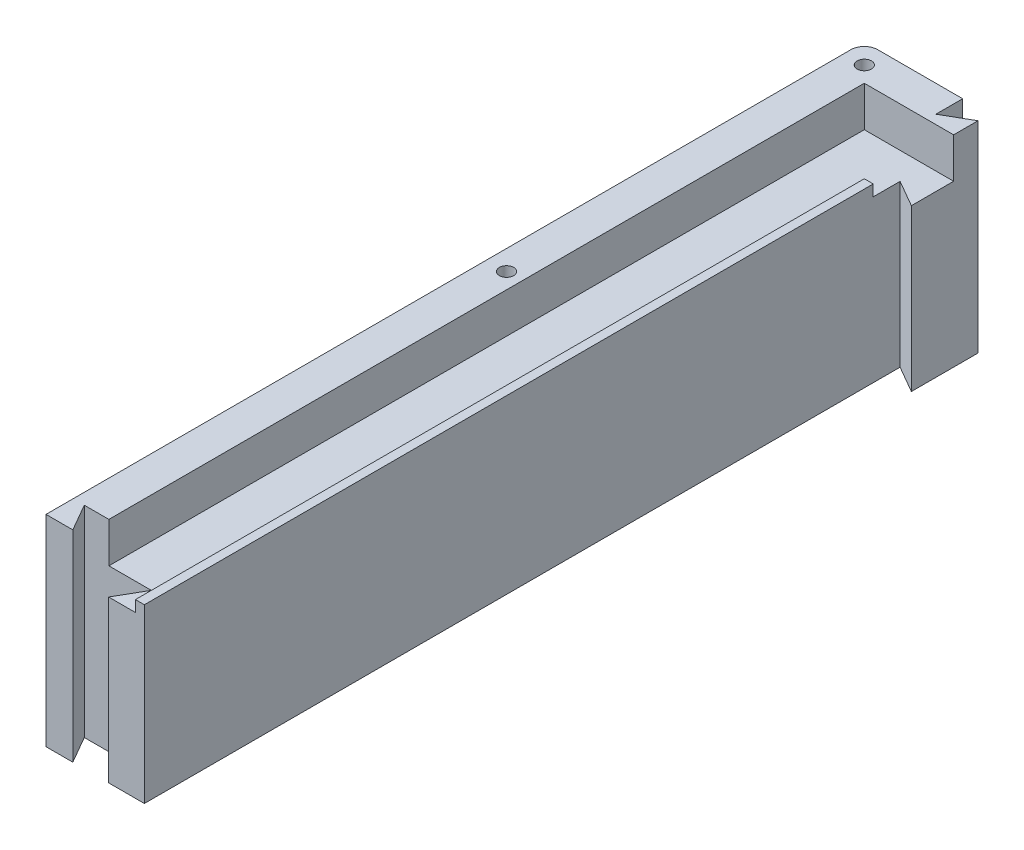
SolidWorks part; units mm, degrees
ref_plane "前视基准面" through (0, 0, 0) normal (0, 0, 1) x (1, 0, 0)
ref_plane "上视基准面" through (0, 0, 0) normal (0, 1, 0) x (1, 0, 0)
ref_plane "右视基准面" through (0, 0, 0) normal (1, 0, 0) x (0, 0, -1)
sketch "草图1" plane through (0, 0, 0) normal (0, 1, 0) x (1, 0, 0)
  line L1 (0, 0) -> (250, 0)
  line L2 (0, 0) -> (0, 350)
  line L3 (0, 350) -> (250, 350)
  line L4 (250, 0) -> (250, 350)
  line L12 (0, 350) -> (-1.1314, 351.1314)
  line L13 (-10, -10) -> (260, -10)
  line L14 (-10, -10) -> (-10, 360)
  line L15 (-10, 360) -> (260, 360)
  line L16 (260, -10) -> (260, 360)
  line L18 (14, 14) -> (236, 14)
  line L19 (14, 14) -> (14, 336)
  line L20 (14, 336) -> (236, 336)
  line L21 (236, 14) -> (236, 336)
  dimension "D7" = 135
  dimension "D1" = 350
  dimension "D2" = 250
  dimension "D3" = 10
  dimension "D4" = 10
  dimension "D5" = 10
  dimension "D6" = 10
  dimension "D8" = 14
  dimension "D9" = 14
  dimension "D10" = 14
  dimension "D11" = 14
extrude "凸台-拉伸2" add sketch "草图1" along normal blind 45
ref_plane "基准面1" through (0, 38.5, 0) normal (0, 1, 0) x (1, 0, 0)
sketch "草图4" plane through (0, 38.5, 0) normal (0, 1, 0) x (1, 0, 0)
  line L0 (0, 0) -> (250, 0) construction
  line L1 (0, 350) -> (250, 350) construction
  line L2 (250, 0) -> (250, 350) construction
  line L3 (0, 0) -> (0, 350) construction
  line L4 (0, 0) -> (250, 0)
  line L5 (0, 350) -> (250, 350)
  line L6 (250, 0) -> (250, 350)
  line L7 (0, 0) -> (0, 350)
  line L9 (14, 14) -> (236, 14)
  line L10 (14, 14) -> (14, 336)
  line L11 (14, 336) -> (236, 336)
  line L12 (236, 14) -> (236, 336)
  dimension "D1" = 14
  dimension "D2" = 14
  dimension "D3" = 14
  dimension "D4" = 14
extrude "凸台-拉伸3" add sketch "草图4" against normal blind 5
sketch "草图9" plane through (0, 38.5, 0) normal (0, 1, 0) x (1, 0, 0)
  line L0 (236, 336) -> (14, 336) construction
  line L1 (236, 14) -> (236, 336) construction
  line L2 (14, 14) -> (236, 14) construction
  line L3 (14, 336) -> (14, 14) construction
  line L4 (0, 350) -> (0, 0)
  line L5 (0, 0) -> (250, 0)
  line L6 (250, 0) -> (250, 350)
  line L7 (250, 350) -> (0, 350)
  line L8 (0, 350) -> (0, 0)
  line L9 (0, 0) -> (250, 0)
  line L10 (250, 0) -> (250, 350)
  line L11 (250, 350) -> (0, 350)
  line L12 (236, 336) -> (14, 336)
  line L13 (236, 14) -> (236, 336)
  line L14 (14, 14) -> (236, 14)
  line L15 (14, 336) -> (14, 14)
  line L16 (238, 12) -> (238, 338)
  line L17 (238, 338) -> (12, 338)
  line L18 (12, 338) -> (12, 12)
  line L19 (12, 12) -> (238, 12)
  line L20 (2, 348) -> (2, 2)
  line L21 (2, 2) -> (248, 2)
  line L22 (248, 2) -> (248, 348)
  line L23 (248, 348) -> (2, 348)
  dimension "D1" = 0
  dimension "D2" = 2
  dimension "D3" = 2
extrude "切除-拉伸3" cut sketch "草图9" against normal blind 2.5 contours L22 L23 L20 L21 L19 L18 L17 L16
sketch "草图12" plane through (0, 45, 0) normal (0, 1, 0) x (1, 0, 0)
  line L0 (0, 350) -> (-10, 360)
  line L1 (-10, 175) -> (260, 175)
  line L2 (-10, -10) -> (-10, 360) construction
  line L3 (260, -10) -> (260, 360) construction
  line L4 (125, -10) -> (125, 360)
  line L5 (-10, -10) -> (260, -10) construction
  line L6 (-10, 360) -> (260, 360) construction
  circle A0 centre (-3.5355, 353.5355) radius 1.6
  circle A1 centre (-3.5355, -3.5355) radius 1.6
  circle A2 centre (253.5355, -3.5355) radius 1.6
  circle A3 centre (253.5355, 353.5355) radius 1.6
  dimension "D1" = 3.2
  dimension "D3" = 5
extrude "切除-拉伸5" cut sketch "草图12" against normal blind 109.5 contours A1 | L0 A0 | L0 A0 | A3 | A2
fillet "圆角1" radius 5 4 edges at (260, 22.5, -360) (260, 22.5, 10) (-10, 22.5, 10) (-10, 22.5, -360)
sketch "草图13" plane through (0, 33.5, 0) normal (0, -1, 0) x (1, 0, 0)
  line L0 (14, -336) -> (14, -14) construction
  line L1 (236, -336) -> (14, -336) construction
  line L2 (14, -14) -> (236, -14) construction
  line L3 (236, -14) -> (236, -336) construction
  line L4 (0, 0) -> (0, -350)
  line L5 (0, -350) -> (250, -350)
  line L6 (250, -350) -> (250, 0)
  line L7 (250, 0) -> (0, 0)
  line L8 (0, 0) -> (0, -350)
  line L9 (0, -350) -> (250, -350)
  line L10 (250, -350) -> (250, 0)
  line L11 (250, 0) -> (0, 0)
  line L12 (14, -336) -> (14, -14)
  line L13 (236, -336) -> (14, -336)
  line L14 (14, -14) -> (236, -14)
  line L15 (236, -14) -> (236, -336)
  dimension "D1" = 0
extrude "凸台-拉伸4" add sketch "草图13" along normal blind 33.5
sketch "草图14" plane through (0, 0, 0) normal (0, -1, 0) x (1, 0, 0)
  line L0 (14, -14) -> (14, 10)
  line L1 (-5, 10) -> (255, 10) construction
  line L2 (236, -14) -> (236, 10)
  line L3 (14, 2) -> (19.9756, 5.45)
  line L4 (19.9756, 5.45) -> (19.9756, -9.45)
  line L5 (19.9756, -9.45) -> (14, -6)
  line L6 (125, 10) -> (125, -14)
  line L7 (236, -14) -> (14, -14) construction
  line L8 (236, 2) -> (230.0244, 5.45)
  line L9 (230.0244, -9.45) -> (236, -6)
  line L10 (230.0244, 5.45) -> (230.0244, -9.45)
  line L11 (14, -175) -> (-10, -175)
  line L12 (14, -14) -> (14, -336) construction
  line L13 (14, -336) -> (14, -360)
  line L14 (14, -352) -> (19.9756, -355.45)
  line L15 (-5, -360) -> (255, -360)
  line L16 (260, -355) -> (260, 5)
  line L17 (255, 10) -> (-5, 10)
  line L18 (-10, 5) -> (-10, -355)
  line L19 (-5, -360) -> (255, -360)
  line L20 (260, -355) -> (260, 5)
  line L21 (255, 10) -> (-5, 10)
  line L22 (-10, 5) -> (-10, -355)
  line L23 (19.9756, -355.45) -> (19.9756, -340.55)
  line L24 (19.9756, -340.55) -> (14, -344)
  line L25 (-2, -175) -> (-5.5, -181.0622)
  line L26 (-5.5, -181.0622) -> (9.5, -181.0622)
  line L27 (9.5, -181.0622) -> (6, -175)
  arc A4 (255, -360) -> (260, -355) centre (255, -355) ccw
  arc A5 (260, 5) -> (255, 10) centre (255, 5) ccw
  arc A6 (-5, 10) -> (-10, 5) centre (-5, 5) ccw
  arc A7 (-10, -355) -> (-5, -360) centre (-5, -355) ccw
  arc A8 (255, -360) -> (260, -355) centre (255, -355) ccw
  arc A9 (260, 5) -> (255, 10) centre (255, 5) ccw
  arc A10 (-5, 10) -> (-10, 5) centre (-5, 5) ccw
  arc A11 (-10, -355) -> (-5, -360) centre (-5, -355) ccw
  point P10 (14, -2)
  point P45 (2, -175)
  circle M15 centre (-3.5355, 3.5355) radius 1.6
  line M16 (-5, -360) -> (255, -360)
  arc M17 (255, -360) -> (260, -355) centre (255, -355) ccw
  line M18 (260, -355) -> (260, 5)
  arc M19 (260, 5) -> (255, 10) centre (255, 5) ccw
  line M20 (255, 10) -> (-5, 10)
  arc M21 (-5, 10) -> (-10, 5) centre (-5, 5) ccw
  line M22 (-10, 5) -> (-10, -355)
  circle M24 centre (253.5355, -353.5355) radius 1.6
  circle M25 centre (253.5355, 3.5355) radius 1.6
  line M26 (236, -14) -> (236, -336)
  line M27 (236, -336) -> (14, -336)
  line M28 (14, -336) -> (14, -14)
  line M29 (14, -14) -> (236, -14)
  dimension "D1" = 4
  dimension "D2" = 4
  dimension "D3" = 60
  dimension "D4" = 60
  dimension "D5" = 14.9
  dimension "D7" = 4
  dimension "D8" = 4
  dimension "D9" = 60
  dimension "D10" = 60
  dimension "D11" = 15
  dimension "D6" = 0
extrude "切除-拉伸10" cut sketch "草图14" against normal blind 126.5 contours L11 L0 M28 M20 M21 M22 M15 | L26 L27 L11 L25 | M15 | L6 L0 L3 L4 L5 M20 M29 | L5 L4 L3 L0 | L10 L8 L2 L6 L9 M20 M29 | L8 L10 L9 L2 | L24 L23 L14 L13 L2 M16 M17 M18 M19 M20 M26 M27 M24 M25 | M25 | M24
sketch "草图15" plane through (0, 45, 0) normal (0, 1, 0) x (1, 0, 0)
  line L0 (12, 358) -> (14, 358)
  line L1 (12, 358) -> (-5, 358)
  line L2 (-8, 355) -> (-8, 177)
  line L3 (-8, 177) -> (-8, 175)
  line L9 (12, 352) -> (12, 352)
  line L10 (14, 352) -> (14, 360)
  line L11 (14, 360) -> (-5, 360)
  line L12 (-10, 355) -> (-10, 175)
  line L13 (-10, 175) -> (-2, 175)
  line L14 (-2, 175) -> (-5.5, 181.0622)
  line L15 (-5.5, 181.0622) -> (0, 181.0622)
  line L16 (0, 181.0622) -> (0, 350)
  line L17 (0, 350) -> (19.9756, 350)
  line L18 (19.9756, 350) -> (19.9756, 355.45)
  line L19 (19.9756, 355.45) -> (14, 352)
  line L20 (14, 352) -> (14, 360)
  line L21 (14, 360) -> (-5, 360)
  line L22 (-10, 355) -> (-10, 175)
  line L23 (-10, 175) -> (-2, 175)
  line L24 (-2, 175) -> (-5.5, 181.0622)
  line L25 (-5.5, 181.0622) -> (0, 181.0622)
  line L26 (0, 181.0622) -> (0, 350)
  line L27 (0, 350) -> (19.9756, 350)
  line L28 (19.9756, 350) -> (19.9756, 355.45)
  line L29 (19.9756, 355.45) -> (14, 352)
  line L30 (12, 352) -> (12, 358) construction
  line L31 (-2, 352) -> (12, 352) construction
  line L32 (-2, 183.0622) -> (-2, 352) construction
  line L33 (12, 352) -> (12, 352) construction
  line L34 (-8.9641, 183.0622) -> (-2, 183.0622) construction
  line L35 (-5.4641, 177) -> (-8.9641, 183.0622) construction
  line L36 (-8, 177) -> (-5.4641, 177) construction
  arc A0 (-5, 358) -> (-8, 355) centre (-5, 355) ccw
  arc A1 (-5, 360) -> (-10, 355) centre (-5, 355) ccw
  arc A2 (-5, 360) -> (-10, 355) centre (-5, 355) ccw
  line M12 (14, 352) -> (14, 360)
  line M13 (14, 360) -> (-5, 360)
  arc M14 (-5, 360) -> (-10, 355) centre (-5, 355) ccw
  line M15 (-10, 355) -> (-10, 175)
  line M16 (-10, 175) -> (-2, 175)
  dimension "D1" = 0
  dimension "D2" = 2
extrude "切除-拉伸11" cut sketch "草图15" against normal blind 46 contours A0 L1 L0 L3 L2 M12 M13 M14 M15 M16
sketch "草图16" plane through (0, 38.5, 0) normal (0, 1, 0) x (1, 0, 0)
  line L6 (19.9756, 348) -> (19.9756, 350)
  line L7 (19.9756, 350) -> (0, 350)
  line L8 (0, 350) -> (0, 181.0622)
  line L9 (0, 181.0622) -> (2, 181.0622)
  line L10 (2, 181.0622) -> (2, 348)
  line L11 (2, 348) -> (19.9756, 348)
  line L12 (19.9756, 348) -> (19.9756, 350)
  line L13 (19.9756, 350) -> (0, 350)
  line L14 (0, 350) -> (0, 181.0622)
  line L15 (0, 181.0622) -> (2, 181.0622)
  line L16 (2, 181.0622) -> (2, 348)
  line L17 (2, 348) -> (19.9756, 348)
  dimension "D1" = 0
extrude "切除-拉伸13" cut sketch "草图16" against normal blind 2.5
sketch "草图17" plane through (0, 45, 0) normal (0, 1, 0) x (1, 0, 0)
  line L0 (-3.5355, 353.5355) -> (-3.5355, 273.5355)
  circle A0 centre (-3.5355, 273.5355) radius 1.6
  dimension "D2" = 3.2
  dimension "D1" = 80
extrude "切除-拉伸14" cut sketch "草图17" against normal blind 75.5
equation "\"2。5\"=10"
